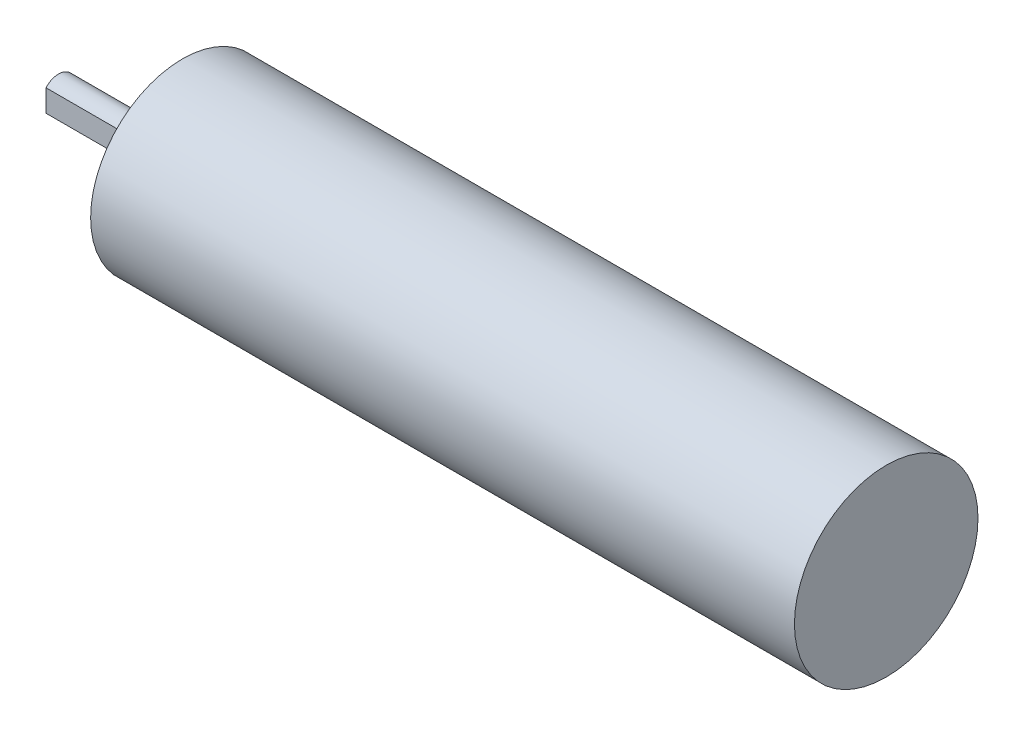
SolidWorks part; units mm, degrees
ref_plane "Front Plane" through (0, 0, 0) normal (0, 0, 1) x (1, 0, 0)
ref_plane "Top Plane" through (0, 0, 0) normal (0, 1, 0) x (1, 0, 0)
ref_plane "Right Plane" through (0, 0, 0) normal (1, 0, 0) x (0, 0, -1)
sketch "Sketch1" plane through (0, 0, 0) normal (0, 0, 1) x (1, 0, 0)
  line L0 (0, 11) -> (0, 0)
  line L1 (0, 0) -> (52.6, 0)
  line L2 (52.6, 0) -> (52.6, 11)
  line L3 (52.6, 11) -> (0, 11)
  line L4 (0, 0) -> (52.6, 0) construction
revolve "Revolve1" add sketch "Sketch1" angle 360 about L4
sketch "Sketch2" plane through (0, 0, 0) normal (-1, 0, 0) x (0, 0, 1)
  circle A0 centre (0, 0) radius 5
extrude "Boss-Extrude1" add sketch "Sketch2" along normal blind 1.35
sketch "Sketch3" plane through (-1.35, 0, 0) normal (-1, 0, 0) x (0, 0, 1)
  circle A0 centre (0, 0) radius 3.5
extrude "Boss-Extrude2" add sketch "Sketch3" along normal blind 1.8
sketch "Sketch4" plane through (-3.15, 0, 0) normal (-1, 0, 0) x (0, 0, 1)
  circle A0 centre (0, 0) radius 2
extrude "Boss-Extrude3" add sketch "Sketch4" along normal blind 11.7
ref_plane "Plane1" through (-3.675, 0, 3.675) normal (0.7071, 0, -0.7071) x (0, 1, 0)
sketch "Sketch6" plane through (-14.85, 0, 0) normal (-1, 0, 0) x (0, 0, 1)
  line L0 (1.5, 1.3229) -> (1.5, -1.3229)
  arc A0 (1.5, -1.3229) -> (1.5, 1.3229) centre (0, 0) ccw
extrude "Cut-Extrude1" cut sketch "Sketch6" against normal up to surface up to plane "Plane1"
hole_wizard "Hole1" positions "Sketch8" profile "Sketch7" legacy
sketch "Sketch8" plane through (0, 0, 0) normal (-1, 0, 0) x (0, 0, 1)
  point P0 (7, 0)
sketch "Sketch7" plane through (0, 0, 7) normal (0, 1, 0) x (0, 0, 1)
  line L0 (0, 0) -> (0, 6.5)
  line L1 (0, 6.5) -> (0.975, 6.5)
  line L2 (0.975, 6.5) -> (0.975, 0)
  line L3 (0.975, 0) -> (0, 0)
  line L4 (0, 110) -> (0, -10) construction
  dimension "Diameter" = 1.95
  dimension "Depth" = 6.5
hole_wizard "Hole2" positions "Sketch10" profile "Sketch9" legacy
sketch "Sketch10" plane through (0, 0, 0) normal (-1, 0, 0) x (0, 0, 1)
  point P0 (-3.5, -6.0622)
sketch "Sketch9" plane through (0, -6.0622, -3.5) normal (0, 1, 0) x (0, 0, 1)
  line L0 (0, 0) -> (0, 6.5)
  line L1 (0, 6.5) -> (0.975, 6.5)
  line L2 (0.975, 6.5) -> (0.975, 0)
  line L3 (0.975, 0) -> (0, 0)
  line L4 (0, 110) -> (0, -10) construction
  dimension "Diameter" = 1.95
  dimension "Depth" = 6.5
hole_wizard "Hole3" positions "Sketch12" profile "Sketch11" legacy
sketch "Sketch12" plane through (0, 0, 0) normal (-1, 0, 0) x (0, 0, 1)
  point P0 (-3.5, 6.0622)
sketch "Sketch11" plane through (0, 6.0622, -3.5) normal (0, 1, 0) x (0, 0, 1)
  line L0 (0, 0) -> (0, 6.5)
  line L1 (0, 6.5) -> (0.975, 6.5)
  line L2 (0.975, 6.5) -> (0.975, 0)
  line L3 (0.975, 0) -> (0, 0)
  line L4 (0, 110) -> (0, -10) construction
  dimension "Diameter" = 1.95
  dimension "Depth" = 6.5
hole_wizard "Hole4" positions "Sketch14" profile "Sketch13" legacy
sketch "Sketch14" plane through (52.6, 0, 0) normal (1, 0, 0) x (0, 0, -1)
  point P0 (0, 0)
sketch "Sketch13" plane through (52.6, 0, 0) normal (0, 1, 0) x (0, 0, -1)
  line L0 (0, 0) -> (0, 6.4)
  line L1 (0, 6.4) -> (3.5, 6.4)
  line L2 (3.5, 6.4) -> (3.5, 0)
  line L3 (3.5, 0) -> (0, 0)
  line L4 (0, 110) -> (0, -10) construction
  dimension "Diameter" = 7
  dimension "Depth" = 6.4
hole_wizard "Hole5" positions "Sketch16" profile "Sketch15" legacy
sketch "Sketch16" plane through (52.6, 0, 0) normal (1, 0, 0) x (0, 0, -1)
  point P0 (-8.5, 0)
sketch "Sketch15" plane through (52.6, 0, 8.5) normal (0, 1, 0) x (0, 0, -1)
  line L0 (0, 0) -> (0, 3)
  line L1 (0, 3) -> (1.05, 3)
  line L2 (1.05, 3) -> (1.05, 0)
  line L3 (1.05, 0) -> (0, 0)
  line L4 (0, 110) -> (0, -10) construction
  dimension "Diameter" = 2.1
  dimension "Depth" = 3
hole_wizard "Hole6" positions "Sketch18" profile "Sketch17" legacy
sketch "Sketch18" plane through (52.6, 0, 0) normal (1, 0, 0) x (0, 0, -1)
  point P0 (4.25, -7.3612)
sketch "Sketch17" plane through (52.6, -7.3612, -4.25) normal (0, 1, 0) x (0, 0, -1)
  line L0 (0, 0) -> (0, 3)
  line L1 (0, 3) -> (1.05, 3)
  line L2 (1.05, 3) -> (1.05, 0)
  line L3 (1.05, 0) -> (0, 0)
  line L4 (0, 110) -> (0, -10) construction
  dimension "Diameter" = 2.1
  dimension "Depth" = 3
hole_wizard "Hole7" positions "Sketch20" profile "Sketch19" legacy
sketch "Sketch20" plane through (52.6, 0, 0) normal (1, 0, 0) x (0, 0, -1)
  point P0 (4.25, 7.3612)
sketch "Sketch19" plane through (52.6, 7.3612, -4.25) normal (0, 1, 0) x (0, 0, -1)
  line L0 (0, 0) -> (0, 3)
  line L1 (0, 3) -> (1.05, 3)
  line L2 (1.05, 3) -> (1.05, 0)
  line L3 (1.05, 0) -> (0, 0)
  line L4 (0, 110) -> (0, -10) construction
  dimension "Diameter" = 2.1
  dimension "Depth" = 3
ref_plane "Plane2" through (52.6, 0, 0) normal (1, 0, 0) x (0, 0, -1)
sketch "Sketch25" plane through (52.6, 0, 0) normal (1, 0, 0) x (0, 0, -1)
  circle A0 centre (0, 0) radius 11
extrude "Boss-Extrude4" add sketch "Sketch25" along normal blind 31.75
